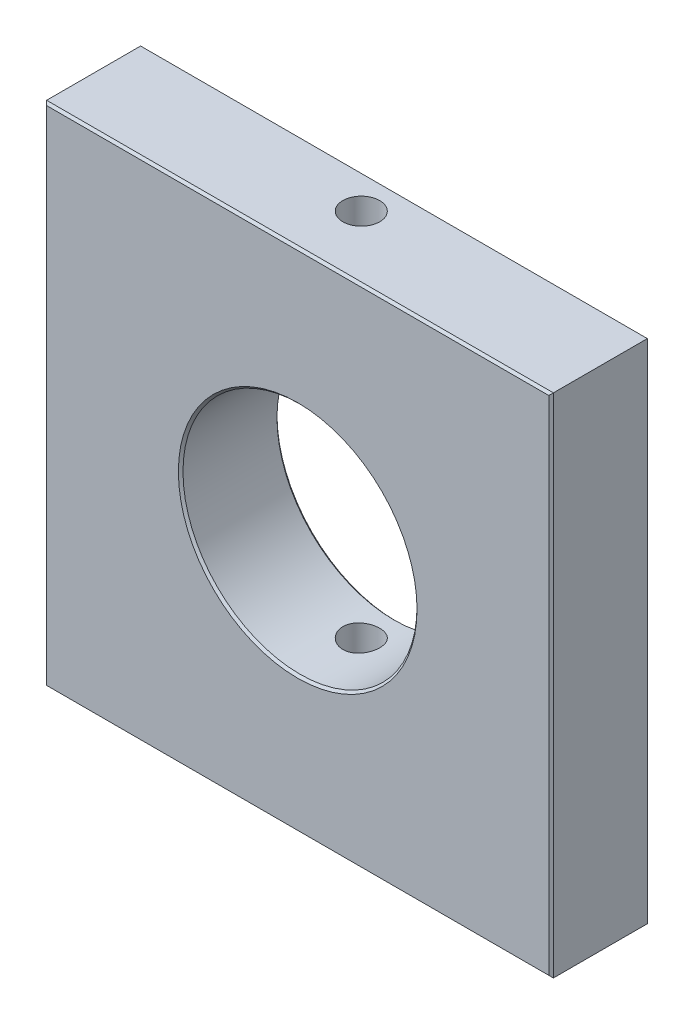
SolidWorks part; units mm, degrees
ref_plane "Front Plane" through (0, 0, 0) normal (0, 0, 1) x (1, 0, 0)
ref_plane "Top Plane" through (0, 0, 0) normal (0, 1, 0) x (1, 0, 0)
ref_plane "Right Plane" through (0, 0, 0) normal (1, 0, 0) x (0, 0, -1)
sketch "Sketch1" plane through (0, 0, 0) normal (0, 0, 1) x (1, 0, 0)
  line L0 (0, 11.646) -> (0, -12.2344) construction
  line L1 (-16.0837, 0) -> (19.3691, 0) construction
  line L3 (-27.5, -27.5) -> (27.5, -27.5)
  line L4 (-27.5, -27.5) -> (-27.5, 27.5)
  line L5 (-27.5, 27.5) -> (27.5, 27.5)
  line L6 (27.5, -27.5) -> (27.5, 27.5)
  line L7 (-27.5, -27.5) -> (27.5, 27.5) construction
  line L8 (-27.5, 27.5) -> (27.5, -27.5) construction
  circle A0 centre (0, 0) radius 12.7
  dimension "D1" = 25.4
  dimension "D2" = 55
  dimension "D3" = 55
extrude "Boss-Extrude1" add sketch "Sketch1" along normal blind 10.7
sketch "Sketch2" plane through (0, 0, 0) normal (0, 1, 0) x (1, 0, 0)
  line L0 (0, 3.8547) -> (0, -9.1116) construction
  line L1 (-11.959, -3.8) -> (12.602, -3.8) construction
  circle A1 centre (0, -3.8) radius 2
  dimension "D2" = 4
  dimension "D1" = 3.8
extrude "Cut-Extrude1" cut sketch "Sketch2" against normal through all both and the other way through all
chamfer "Chamfer1" distance 0.25 angle 45 10 edges at (12.7, 0, 10.7) (0, -27.5, 10.7) (-27.5, 0, 10.7) (0, 27.5, 10.7) (27.5, 0, 10.7) (12.7, 0, 0) (0, 27.5, 0) (-27.5, 0, 0) (0, -27.5, 0) (27.5, 0, 0)
